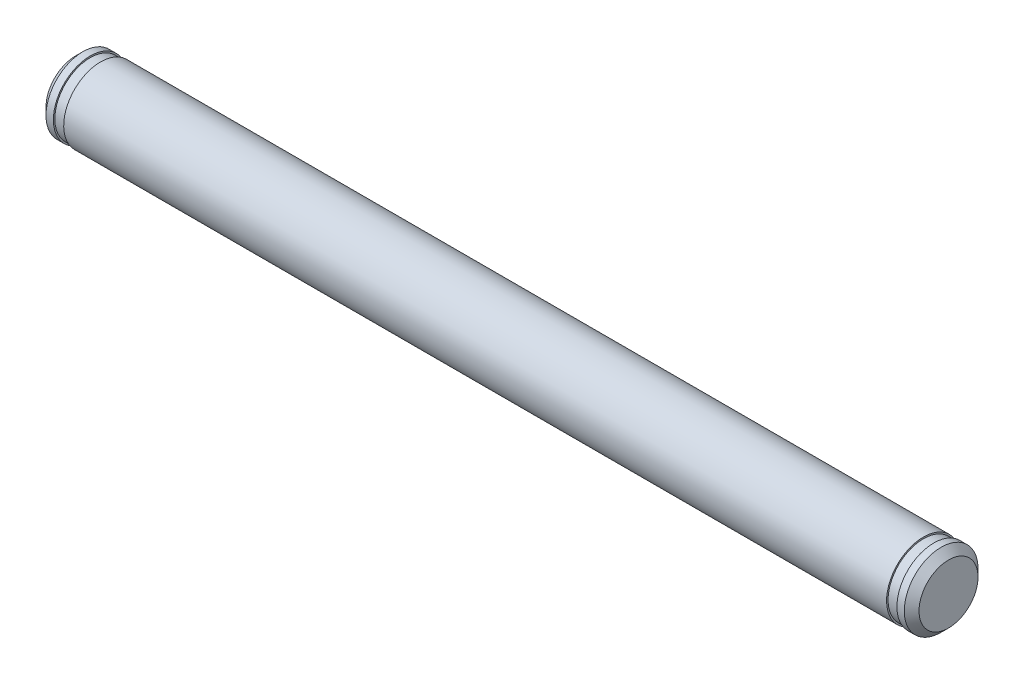
SolidWorks part; units mm, degrees
ref_plane "前视基准面" through (0, 0, 0) normal (0, 0, 1) x (1, 0, 0)
ref_plane "上视基准面" through (0, 0, 0) normal (0, 1, 0) x (1, 0, 0)
ref_plane "右视基准面" through (0, 0, 0) normal (1, 0, 0) x (0, 0, -1)
other "Configuration Table"
sketch "草图1" plane through (0, 0, 0) normal (0, 0, 1) x (1, 0, 0)
  line L0 (-0.2254, 0) -> (29.6, 0) construction
  line L1 (29.6, 0) -> (29.6, 2.5)
  line L2 (29.6, 2.5) -> (28.6, 2.5)
  line L3 (28.6, 2.5) -> (28.6, 2.4)
  line L4 (28.6, 2.4) -> (27.9, 2.4)
  line L5 (27.9, 2.4) -> (27.9, 2.5)
  line L6 (27.9, 2.5) -> (-27.9, 2.5)
  line L7 (0, 2.5) -> (0, 0) construction
  line L8 (0.2254, 0) -> (-29.6, 0) construction
  line L9 (-29.6, 0) -> (-29.6, 2.5)
  line L10 (-27.9, 2.4) -> (-27.9, 2.5)
  line L11 (-28.6, 2.4) -> (-27.9, 2.4)
  line L12 (-28.6, 2.5) -> (-28.6, 2.4)
  line L13 (-29.6, 2.5) -> (-28.6, 2.5)
  line L14 (29.6, 0) -> (-29.6, 0)
  line L15 (28, 2.4) -> (28, 0) construction
  line L16 (-28, 2.4) -> (-28, 0) construction
  dimension "D1" = 5
  dimension "D2" = 4.8
  dimension "D3" = 0.7
  dimension "D4" = 1
  dimension "D5" = 0.6
  dimension "D6" = 56
revolve "旋转1" add sketch "草图1" angle 360 about L14
chamfer "倒角1" distance 0.5 angle 45 2 edges at (29.6, 2.5, 0) (-29.6, 2.5, 0)
ref_plane "基准面1" through (-28, 0, 0) normal (-1, 0, 0) x (0, 0, 1)
